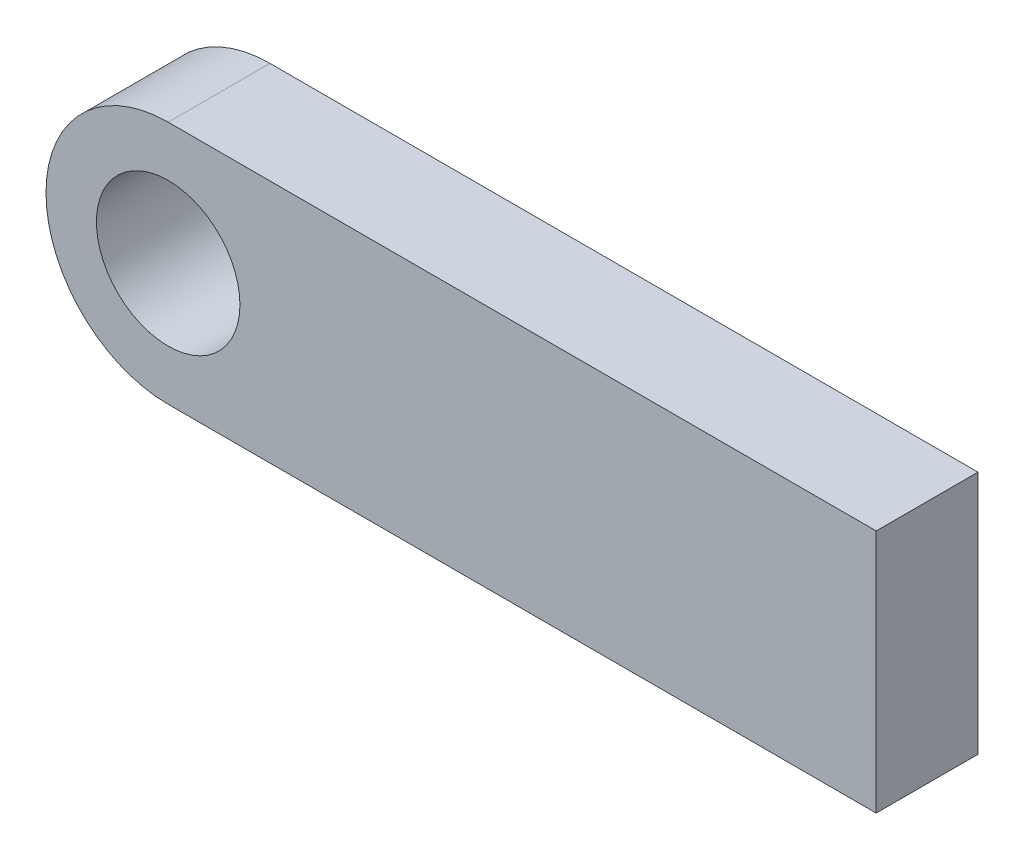
SolidWorks part; units mm, degrees
ref_plane "前视基准面" through (0, 0, 0) normal (0, 0, 1) x (1, 0, 0)
ref_plane "上视基准面" through (0, 0, 0) normal (0, 1, 0) x (1, 0, 0)
ref_plane "右视基准面" through (0, 0, 0) normal (1, 0, 0) x (0, 0, -1)
sketch "草图1" plane through (0, 0, 0) normal (0, 0, 1) x (1, 0, 0)
  line L0 (0, 6) -> (34.7702, 6)
  line L1 (34.7702, 6) -> (34.7702, -6)
  line L6 (34.7702, -6) -> (0, -6)
  arc A4 (0, 6) -> (0, -6) centre (0, 0) ccw
  circle A5 centre (0, 0) radius 3.5247
  dimension "D3" = 12
extrude "凸台-拉伸1" add sketch "草图1" along normal mid plane 5
